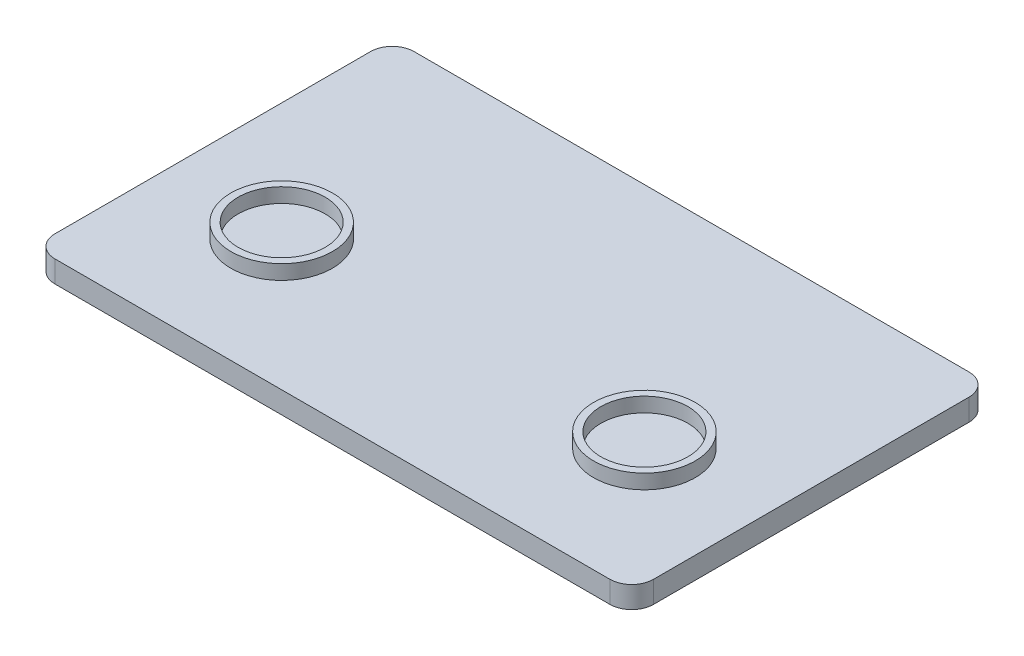
SolidWorks part; units mm, degrees
ref_plane "Front Plane" through (0, 0, 0) normal (0, 0, 1) x (1, 0, 0)
ref_plane "Top Plane" through (0, 0, 0) normal (0, 1, 0) x (1, 0, 0)
ref_plane "Right Plane" through (0, 0, 0) normal (1, 0, 0) x (0, 0, -1)
sketch "Sketch1" plane through (0, 0, 0) normal (0, 1, 0) x (1, 0, 0)
  line L0 (-65.0781, 0) -> (65.9876, 0) construction
  line L1 (0, -35.6959) -> (0, 42.4227) construction
  line L3 (-38.25, 24.75) -> (38.25, 24.75)
  line L4 (-41.25, 21.75) -> (-41.25, -21.75)
  line L5 (-38.25, -24.75) -> (38.25, -24.75)
  line L6 (41.25, 21.75) -> (41.25, -21.75)
  line L7 (-41.25, 24.75) -> (41.25, -24.75) construction
  line L8 (-41.25, -24.75) -> (41.25, 24.75) construction
  arc A0 (38.25, 24.75) -> (41.25, 21.75) centre (38.25, 21.75) cw
  arc A1 (38.25, -24.75) -> (41.25, -21.75) centre (38.25, -21.75) ccw
  arc A2 (-41.25, -21.75) -> (-38.25, -24.75) centre (-38.25, -21.75) ccw
  arc A3 (-38.25, 24.75) -> (-41.25, 21.75) centre (-38.25, 21.75) ccw
  point P5 (0, 0)
  dimension "D3" = 3
  dimension "D1" = 82.5
  dimension "D2" = 49.5
extrude "Boss-Extrude1" add sketch "Sketch1" along normal blind 3
sketch "Sketch2" plane through (0, 3, 0) normal (0, 1, 0) x (1, 0, 0)
  line L0 (-74.182, -6.75) -> (52.5133, -6.75) construction
  line L1 (0, -31.9126) -> (0, 30.4801) construction
  line L2 (-38.25, -24.75) -> (38.25, -24.75) construction
  circle A0 centre (-25, -6.75) radius 7
  circle A1 centre (-25, -6.75) radius 6
  circle A2 centre (25, -6.75) radius 6
  circle A3 centre (25, -6.75) radius 7
  dimension "D2" = 14
  dimension "D1" = 18
  dimension "D3" = 25
extrude "Boss-Extrude2" add sketch "Sketch2" along normal blind 2
